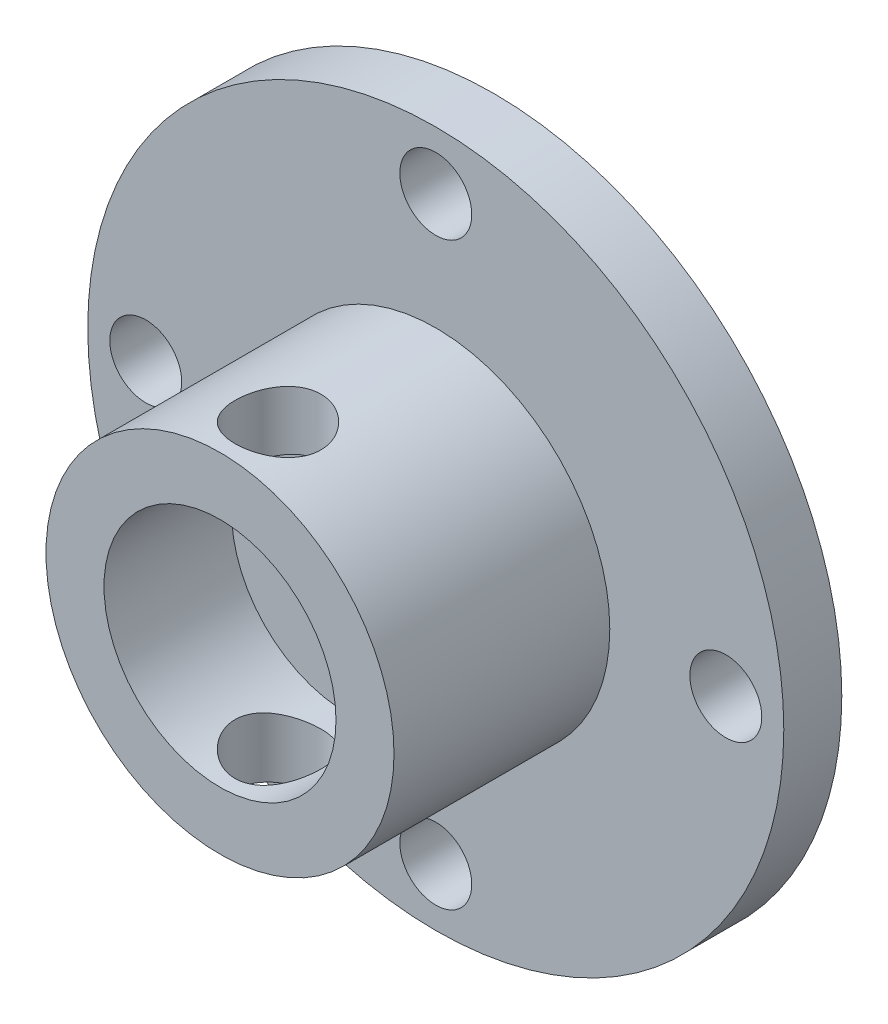
SolidWorks part; units mm, degrees
ref_plane "Front Plane" through (0, 0, 0) normal (0, 0, 1) x (1, 0, 0)
ref_plane "Top Plane" through (0, 0, 0) normal (0, 1, 0) x (1, 0, 0)
ref_plane "Right Plane" through (0, 0, 0) normal (1, 0, 0) x (0, 0, -1)
sketch "Sketch1" plane through (0, 0, 0) normal (0, 0, 1) x (1, 0, 0)
  circle A0 centre (0, 0) radius 12.5 construction
  circle A3 centre (0, 0) radius 15
  circle A4 centre (0, 12.5) radius 1.55
  circle A5 centre (12.5, 0) radius 1.55
  circle A6 centre (0, -12.5) radius 1.55
  circle A7 centre (-12.5, 0) radius 1.55
  point P15 (0, 0)
  dimension "D1" = 25
  dimension "D2" = 30
  dimension "D3" = 3.1
  dimension "D4" = 4
extrude "Boss-Extrude1" add sketch "Sketch1" along normal blind 2.5
sketch "Sketch3" plane through (0, 0, 0) normal (0, 0, 1) x (1, 0, 0)
  circle A0 centre (0, 0) radius 7.5
  dimension "D1" = 15
extrude "Boss-Extrude2" add sketch "Sketch3" along normal blind 9.3 from surface at 2.5 starting at face at (1.55, -12.5, 2.5)
sketch "Sketch4" plane through (0, 0, 11.8) normal (0, 0, 1) x (1, 0, 0)
  circle A0 centre (0, 0) radius 2.5
  dimension "D1" = 5
extrude "Cut-Extrude1" cut sketch "Sketch4" against normal through all both and the other way through all
sketch "Sketch5" plane through (0, 0, 11.8) normal (0, 0, 1) x (1, 0, 0)
  circle A0 centre (0, 0) radius 5
  dimension "D1" = 10
extrude "Cut-Extrude2" cut sketch "Sketch5" against normal blind 5.5
sketch "Sketch6" plane through (0, 0, 0) normal (0, 1, 0) x (1, 0, 0)
  line L0 (-7.5, -11.8) -> (7.5, -11.8) construction
  circle A0 centre (0, -9.3) radius 1.85
  dimension "D1" = 3.7
  dimension "D2" = 2.5
extrude "Cut-Extrude3" cut sketch "Sketch6" against normal through all both and the other way through all
